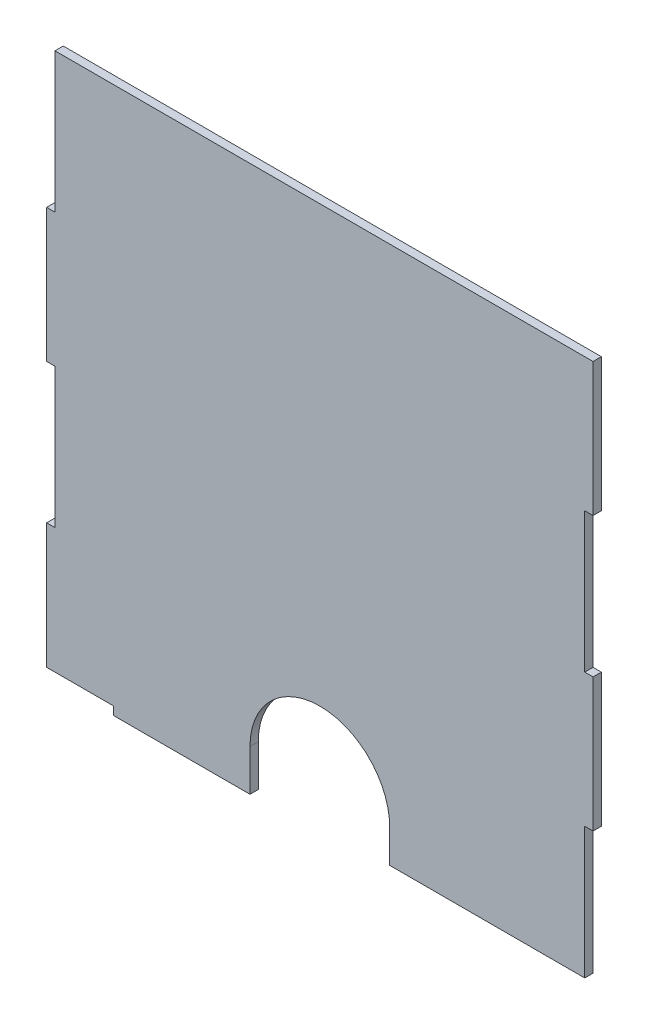
SolidWorks part; units mm, degrees
ref_plane "Front Plane" through (0, 0, 0) normal (0, 0, 1) x (1, 0, 0)
ref_plane "Top Plane" through (0, 0, 0) normal (0, 1, 0) x (1, 0, 0)
ref_plane "Right Plane" through (0, 0, 0) normal (1, 0, 0) x (0, 0, -1)
sketch "Sketch1" plane through (0, 0, 0) normal (0, 0, 1) x (1, 0, 0)
  line L0 (0, -197.5) -> (0, -167.5) construction
  line L1 (-197.5, -197.5) -> (197.5, -197.5)
  line L2 (-197.5, -197.5) -> (-197.5, 197.5)
  line L3 (-197.5, 197.5) -> (197.5, 197.5)
  line L4 (197.5, -197.5) -> (197.5, 197.5)
  line L5 (-197.5, -197.5) -> (197.5, 197.5) construction
  line L6 (-197.5, 197.5) -> (197.5, -197.5) construction
  line L7 (-50.5, -227.5) -> (50.5, -227.5)
  line L8 (-50.5, -227.5) -> (-50.5, -167.5)
  line L10 (50.5, -227.5) -> (50.5, -167.5)
  line L11 (-50.5, -227.5) -> (50.5, -167.5) construction
  line L12 (-50.5, -167.5) -> (50.5, -227.5) construction
  line L14 (-197.5, -197.5) -> (-149, -197.5)
  line L15 (-197.5, -197.5) -> (-197.5, -191.5)
  line L16 (-197.5, -191.5) -> (-149, -191.5)
  line L17 (-149, -197.5) -> (-149, -191.5)
  line L18 (-197.5, 197.5) -> (-191.5, 197.5)
  line L19 (-197.5, 197.5) -> (-197.5, 96.5)
  line L20 (-197.5, 96.5) -> (-191.5, 96.5)
  line L21 (-191.5, 197.5) -> (-191.5, 96.5)
  line L22 (197.5, -197.5) -> (191.5, -197.5)
  line L23 (197.5, -197.5) -> (197.5, -96.5)
  line L24 (197.5, -96.5) -> (191.5, -96.5)
  line L25 (191.5, -197.5) -> (191.5, -96.5)
  line L26 (-197.5, 0) -> (-191.5, 0)
  line L27 (-197.5, 0) -> (-197.5, -101)
  line L28 (-197.5, -101) -> (-191.5, -101)
  line L29 (-191.5, 0) -> (-191.5, -101)
  line L30 (197.5, 0) -> (191.5, 0)
  line L31 (197.5, 0) -> (197.5, 101)
  line L32 (197.5, 101) -> (191.5, 101)
  line L33 (191.5, 0) -> (191.5, 101)
  line L34 (48, -197.5) -> (191.5, -197.5)
  line L35 (48, -197.5) -> (48, -191.5)
  line L36 (48, -191.5) -> (191.5, -191.5)
  line L37 (191.5, -197.5) -> (191.5, -191.5)
  circle A0 centre (0, -167.5) radius 50.5
  point P0 (0, 0)
  point P6 (0, -197.5)
  dimension "D1" = 395
  dimension "D2" = 101
  dimension "D3" = 30
  dimension "D4" = 6
  dimension "D5" = 101
  dimension "D6" = 143.5
  dimension "D7" = 6
  dimension "D8" = 48.5
extrude "Boss-Extrude1" add sketch "Sketch1" along normal blind 6 contours A0 L10 L1 L25 L24 L4 L30 L33 L32 L3 L21 L20 L2 L26 L29 L28 L16 L17 L8
